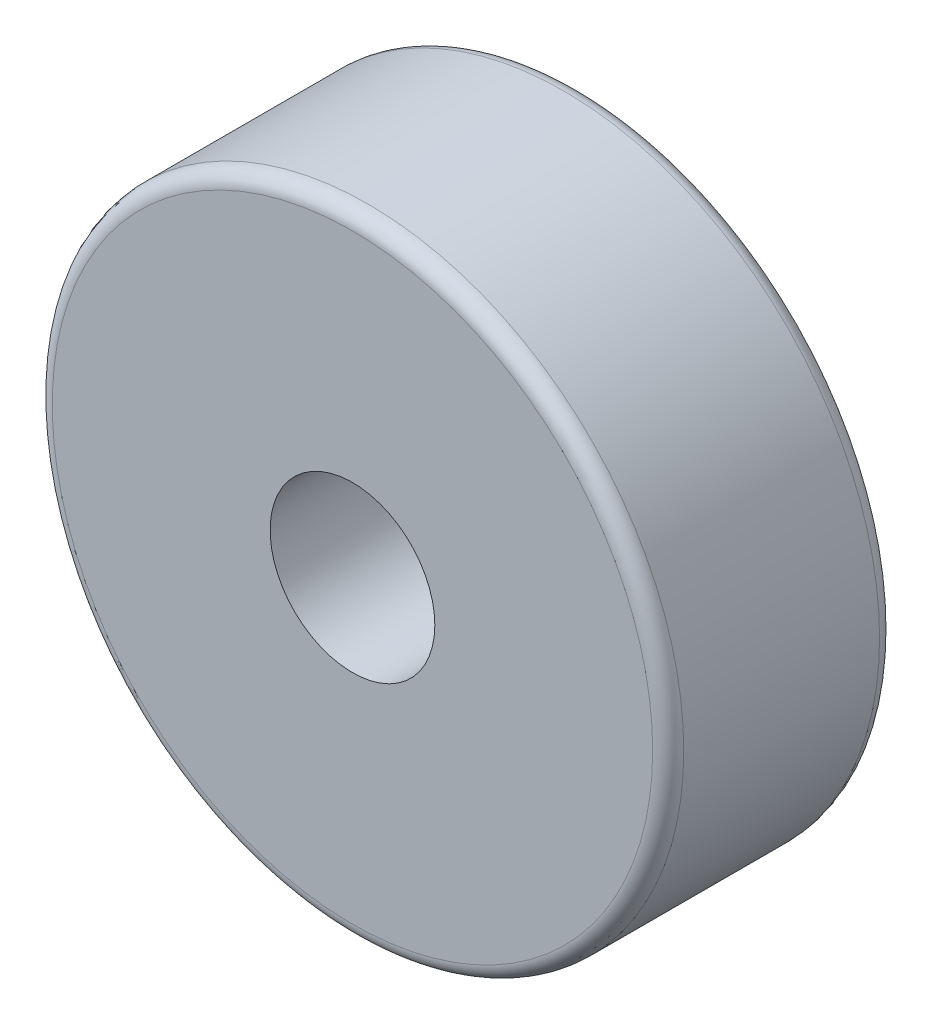
SolidWorks part; units mm, degrees
ref_plane "Plan de face" through (0, 0, 0) normal (0, 0, 1) x (1, 0, 0)
ref_plane "Plan de dessus" through (0, 0, 0) normal (0, 1, 0) x (1, 0, 0)
ref_plane "Plan de droite" through (0, 0, 0) normal (1, 0, 0) x (0, 0, -1)
sketch "Esquisse1" plane through (0, 0, 0) normal (0, 0, 1) x (1, 0, 0)
  circle A0 centre (0, 0) radius 101.6
  circle A1 centre (0, 0) radius 26.5
  dimension "D1" = 203.2
  dimension "D2" = 53
extrude "Boss.-Extru.1" add sketch "Esquisse1" along normal blind 73
fillet "Congé1" radius 5 2 edges at (101.6, 0, 0) (101.6, 0, 73)
